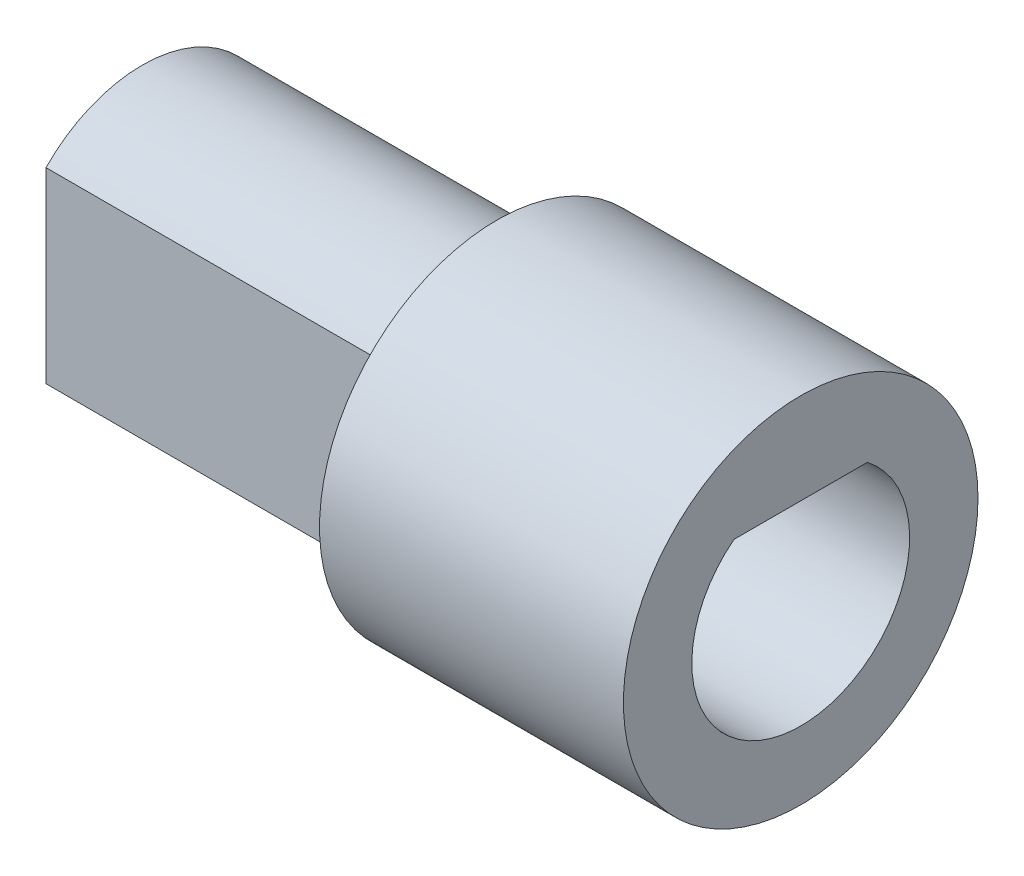
SolidWorks part; units mm, degrees
ref_plane "Front Plane" through (0, 0, 0) normal (0, 0, 1) x (1, 0, 0)
ref_plane "Top Plane" through (0, 0, 0) normal (0, 1, 0) x (1, 0, 0)
ref_plane "Right Plane" through (0, 0, 0) normal (1, 0, 0) x (0, 0, -1)
sketch "Sketch1" plane through (0, 0, 0) normal (1, 0, 0) x (0, 0, -1)
  line L0 (-1.9, 1.8473) -> (-1.9, -1.8473)
  line L1 (1.9, 1.8473) -> (1.9, -1.8473)
  arc A0 (-1.9, -1.8473) -> (1.9, -1.8473) centre (0, 0) ccw
  arc A2 (1.9, 1.8473) -> (-1.9, 1.8473) centre (0, 0) ccw
  point P1 (0, 0)
  dimension "D3" = 5.3
  dimension "D1" = 3.8
  dimension "D2" = 1.9
sketch "Sketch5" plane through (0, 0, 0) normal (1, 0, 0) x (0, 0, -1)
  line L0 (-1.3162, 1.7) -> (1.3162, 1.7) construction
  arc A0 (-1.3162, 1.7) -> (1.3162, 1.7) centre (0, 0) ccw construction
  circle A1 centre (0, 0) radius 3.5
  dimension "D1" = 4.3
  dimension "D3" = 7
  dimension "D2" = 1.7
extrude "Boss-Extrude1" add sketch "Sketch1" against normal blind 7
extrude "Boss-Extrude2" add sketch "Sketch5" along normal blind 6 contours A1
fillet "Fillet1" radius 0.5 4 edges at (0, 0, -1.9) (0, -2.65, 0) (0, 0, 1.9) (0, 2.65, 0)
sketch "Sketch7" plane through (6, 0, 0) normal (1, 0, 0) x (0, 0, -1)
  line L0 (-1.3162, 1.7) -> (1.3162, 1.7)
  arc A0 (-1.3162, 1.7) -> (1.3162, 1.7) centre (0, 0) ccw
  arc A1 (-1.3162, 1.7) -> (1.3162, 1.7) centre (0, 0) ccw construction
extrude "Cut-Extrude1" cut sketch "Sketch7" against normal blind 5
equation "\"D2@Sketch1\"=\"D1@Sketch1\"/2"
